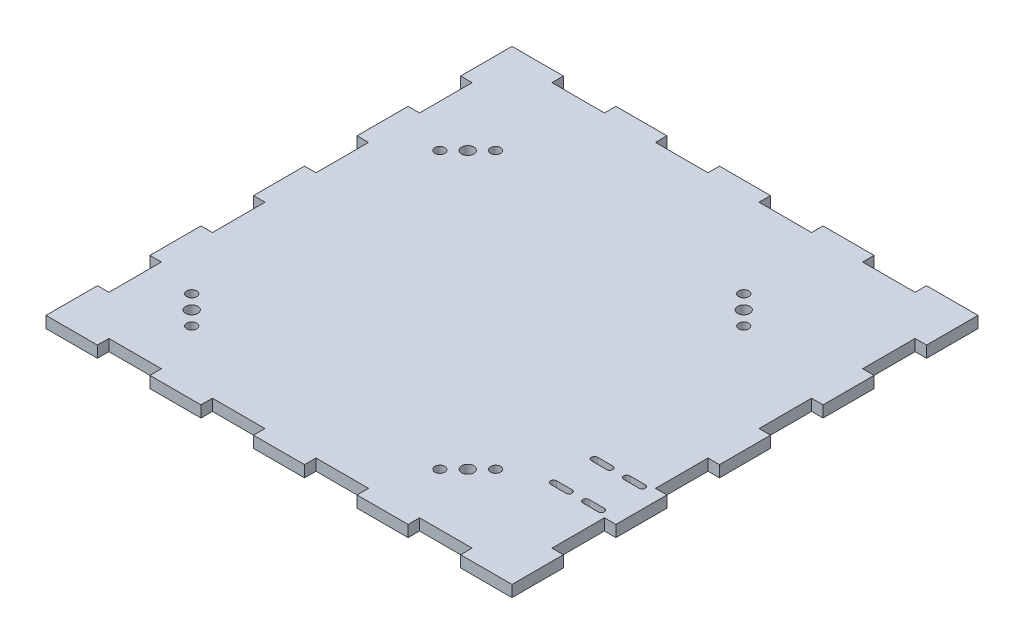
SolidWorks part; units mm, degrees
ref_plane "Front Plane" through (0, 0, 0) normal (0, 0, 1) x (1, 0, 0)
ref_plane "Top Plane" through (0, 0, 0) normal (0, 1, 0) x (1, 0, 0)
ref_plane "Right Plane" through (0, 0, 0) normal (1, 0, 0) x (0, 0, -1)
sketch "Board" plane through (0, 0, 0) normal (0, 1, 0) x (1, 0, 0)
  line L0 (45, -19.76) -> (50, -19.76)
  line L1 (-42.5, -42.5) -> (42.5, -42.5)
  line L2 (-42.5, -42.5) -> (-42.5, 42.5)
  line L3 (-42.5, 42.5) -> (42.5, 42.5)
  line L4 (42.5, -42.5) -> (42.5, 42.5)
  line L5 (-42.5, -42.5) -> (42.5, 42.5) construction
  line L6 (-42.5, 42.5) -> (42.5, -42.5) construction
  line L7 (-50.8, 48.85) -> (50.8, 48.85)
  line L8 (-50.8, 48.85) -> (-50.8, 42.5)
  line L9 (-50.8, 42.5) -> (50.8, 42.5)
  line L10 (50.8, 48.85) -> (50.8, 42.5)
  line L11 (45, -27.76) -> (50, -27.76)
  line L12 (47.5, -27.76) -> (47.5, -19.76) construction
  circle A0 centre (-38.5, 38.5) radius 1.6
  circle A1 centre (-38.5, -38.5) radius 1.6
  circle A2 centre (38.5, -38.5) radius 1.6
  circle A3 centre (38.5, 38.5) radius 1.6
  point P0 (0, 0)
  point P14 (0, 42.5)
  point P15 (0, 42.5)
  point P26 (47.5, -23.76)
  dimension "D4" = 3.2
  dimension "D1" = 85
  dimension "D2" = 85
  dimension "D3" = 4
  dimension "D5" = 6.35
  dimension "D6" = 101.6
  dimension "D7" = 18.74
  dimension "D8" = 8
  dimension "D9" = 5
  dimension "D10" = 5
sketch "Sketch2" plane through (0, 0, 0) normal (0, 1, 0) x (1, 0, 0)
  line L0 (-42.5, -42.5) -> (-42.5, 42.5) construction
  line L1 (-54.3, 66.65) -> (69.3, 66.65) construction
  line L2 (-54.3, 66.65) -> (-54.3, -56.95) construction
  line L3 (-54.3, -56.95) -> (69.3, -56.95) construction
  line L4 (69.3, 66.65) -> (69.3, -56.95) construction
  line L6 (42.5, -42.5) -> (42.5, 42.5) construction
  line L7 (-50.8, 48.85) -> (50.8, 48.85) construction
  line L8 (-57.5, 69.85) -> (-57.5, -60.15)
  line L9 (-57.5, -60.15) -> (72.5, -60.15)
  line L10 (72.5, 69.85) -> (72.5, -60.15)
  line L11 (-57.5, 69.85) -> (72.5, 69.85)
  circle A0 centre (-38.5, 38.5) radius 1.7
  circle A1 centre (-38.5, -38.5) radius 1.7
  circle A2 centre (38.5, -38.5) radius 1.7
  circle A3 centre (38.5, 38.5) radius 1.7
  point P16 (0, 0)
  dimension "D1" = 3.4
  dimension "D2" = 15
  dimension "D3" = 21
  dimension "D4" = 30
  dimension "D6" = 130
  dimension "D5" = 3.2
extrude "Boss-Extrude1" add sketch "Sketch2" along normal blind 3.2
sketch "Sketch5" plane through (0, 3.2, 0) normal (0, 1, 0) x (1, 0, 0)
  line L0 (34.6109, 42.3891) -> (42.3891, 34.6109) construction
  line L1 (72.5, -60.15) -> (72.5, 69.85) construction
  circle A0 centre (42.3891, 34.6109) radius 1.4
  circle A1 centre (34.6109, 42.3891) radius 1.4
  circle A2 centre (34.6109, -42.3891) radius 1.4
  circle A3 centre (42.3891, -34.6109) radius 1.4
  circle A4 centre (-42.3891, -34.6109) radius 1.4
  circle A5 centre (-34.6109, -42.3891) radius 1.4
  circle A6 centre (-34.6109, 42.3891) radius 1.4
  circle A7 centre (-42.3891, 34.6109) radius 1.4
  point P4 (38.5, 38.5)
  point P7 (-39.8129, -47.5911)
  point P8 (0, 0)
  point P23 (0, 0)
  dimension "D3" = 2.8
  dimension "D1" = 45
  dimension "D2" = 11
extrude "Cut-Extrude2" cut sketch "Sketch5" against normal up to next
sketch "Sketch4" plane through (0, 3.2, 0) normal (0, 1, 0) x (1, 0, 0)
  line L0 (72.5, 55.4056) -> (72.5, 40.9611)
  line L1 (72.5, -60.15) -> (72.5, 69.85) construction
  line L2 (72.5, 12.0722) -> (69.3, 12.0722)
  line L3 (69.3, 12.0722) -> (69.3, 26.5167)
  line L4 (69.3, 26.5167) -> (72.5, 26.5167)
  line L5 (72.5, 26.5167) -> (72.5, 12.0722)
  line L6 (72.5, -16.8167) -> (69.3, -16.8167)
  line L7 (69.3, -16.8167) -> (69.3, -2.3722)
  line L8 (69.3, -2.3722) -> (72.5, -2.3722)
  line L9 (72.5, -2.3722) -> (72.5, -16.8167)
  line L10 (72.5, 40.9611) -> (69.3, 40.9611)
  line L11 (69.3, 40.9611) -> (69.3, 55.4056)
  line L12 (69.3, 55.4056) -> (72.5, 55.4056)
  line L13 (72.5, -45.7056) -> (69.3, -45.7056)
  line L14 (69.3, -45.7056) -> (69.3, -31.2611)
  line L15 (69.3, -31.2611) -> (72.5, -31.2611)
  line L16 (72.5, -31.2611) -> (72.5, -45.7056)
  line L17 (72.5, 40.9611) -> (72.5, 12.0722) construction
  line L18 (69.3, -45.7056) -> (69.3, -60.15) construction
  line L19 (-57.5, -60.15) -> (72.5, -60.15) construction
  line L20 (69.3, -31.2611) -> (69.3, -16.8167) construction
  line L21 (72.5, 69.85) -> (-57.5, 69.85) construction
  line L42 (-57.5, 69.85) -> (72.5, -60.15) construction
  line L66 (-43.0556, -60.15) -> (-43.0556, -56.95)
  line L67 (-43.0556, -56.95) -> (-28.6111, -56.95)
  line L68 (-28.6111, -56.95) -> (-28.6111, -60.15)
  line L91 (69.3, -2.3722) -> (69.3, 12.0722) construction
  line L92 (69.3, 26.5167) -> (69.3, 40.9611) construction
  line L93 (69.3, 55.4056) -> (69.3, 69.85) construction
  line L94 (-28.6111, -60.15) -> (-43.0556, -60.15)
  line L95 (-14.1667, -60.15) -> (-14.1667, -56.95)
  line L96 (-14.1667, -56.95) -> (0.2778, -56.95)
  line L97 (0.2778, -56.95) -> (0.2778, -60.15)
  line L103 (0.2778, -60.15) -> (-14.1667, -60.15)
  line L108 (14.7222, -60.15) -> (14.7222, -56.95)
  line L113 (14.7222, -56.95) -> (29.1667, -56.95)
  line L118 (29.1667, -56.95) -> (29.1667, -60.15)
  line L119 (29.1667, -60.15) -> (14.7222, -60.15)
  line L120 (58.0556, -60.15) -> (43.6111, -60.15)
  line L121 (43.6111, -60.15) -> (43.6111, -56.95)
  line L125 (43.6111, -56.95) -> (58.0556, -56.95)
  line L126 (58.0556, -56.95) -> (58.0556, -60.15)
  line L127 (-57.5, 55.4056) -> (-54.3, 55.4056)
  line L128 (-54.3, 55.4056) -> (-54.3, 40.9611)
  line L129 (-54.3, 40.9611) -> (-57.5, 40.9611)
  line L130 (-57.5, 40.9611) -> (-57.5, 55.4056)
  line L131 (-57.5, 26.5167) -> (-54.3, 26.5167)
  line L132 (-54.3, 26.5167) -> (-54.3, 12.0722)
  line L133 (-54.3, 12.0722) -> (-57.5, 12.0722)
  line L134 (-57.5, 12.0722) -> (-57.5, 26.5167)
  line L135 (-57.5, -2.3722) -> (-54.3, -2.3722)
  line L136 (-54.3, -2.3722) -> (-54.3, -16.8167)
  line L137 (-54.3, -16.8167) -> (-57.5, -16.8167)
  line L138 (-57.5, -16.8167) -> (-57.5, -2.3722)
  line L139 (-57.5, -45.7056) -> (-57.5, -31.2611)
  line L140 (-57.5, -31.2611) -> (-54.3, -31.2611)
  line L141 (-54.3, -31.2611) -> (-54.3, -45.7056)
  line L142 (-54.3, -45.7056) -> (-57.5, -45.7056)
  line L143 (58.0556, 69.85) -> (58.0556, 66.65)
  line L144 (58.0556, 66.65) -> (43.6111, 66.65)
  line L145 (43.6111, 66.65) -> (43.6111, 69.85)
  line L146 (43.6111, 69.85) -> (58.0556, 69.85)
  line L147 (29.1667, 69.85) -> (29.1667, 66.65)
  line L148 (29.1667, 66.65) -> (14.7222, 66.65)
  line L149 (14.7222, 66.65) -> (14.7222, 69.85)
  line L150 (14.7222, 69.85) -> (29.1667, 69.85)
  line L151 (0.2778, 69.85) -> (0.2778, 66.65)
  line L152 (0.2778, 66.65) -> (-14.1667, 66.65)
  line L153 (-14.1667, 66.65) -> (-14.1667, 69.85)
  line L154 (-14.1667, 69.85) -> (0.2778, 69.85)
  line L155 (-43.0556, 69.85) -> (-28.6111, 69.85)
  line L156 (-28.6111, 69.85) -> (-28.6111, 66.65)
  line L157 (-28.6111, 66.65) -> (-43.0556, 66.65)
  line L158 (-43.0556, 66.65) -> (-43.0556, 69.85)
  point P27 (7.5, 4.85)
  point P81 (7.5, 4.85)
  dimension "D4" = 3.2
  dimension "D1" = 4
  dimension "D2" = 4
extrude "Cut-Extrude1" cut sketch "Sketch4" against normal through all
sketch "Sketch6" plane through (0, 3.2, 0) normal (0, 1, 0) x (1, 0, 0)
  line L0 (67, -29.7389) -> (62.7, -29.7389) construction
  line L1 (67, -30.5889) -> (62.7, -30.5889)
  line L2 (67, -28.8889) -> (62.7, -28.8889)
  line L3 (58, -29.7389) -> (53.7, -29.7389) construction
  line L4 (58, -30.5889) -> (53.7, -30.5889)
  line L5 (58, -28.8889) -> (53.7, -28.8889)
  line L6 (72.5, -24.0389) -> (-49927.5, -24.0389) construction
  line L7 (72.5, -31.2611) -> (72.5, -16.8167) construction
  line L8 (58, -18.3389) -> (53.7, -18.3389) construction
  line L9 (58, -17.4889) -> (53.7, -17.4889)
  line L10 (58, -19.1889) -> (53.7, -19.1889)
  line L11 (67, -18.3389) -> (62.7, -18.3389) construction
  line L12 (67, -17.4889) -> (62.7, -17.4889)
  line L13 (67, -19.1889) -> (62.7, -19.1889)
  arc A0 (67, -30.5889) -> (67, -28.8889) centre (67, -29.7389) ccw
  arc A1 (62.7, -28.8889) -> (62.7, -30.5889) centre (62.7, -29.7389) ccw
  arc A2 (58, -30.5889) -> (58, -28.8889) centre (58, -29.7389) ccw
  arc A3 (53.7, -28.8889) -> (53.7, -30.5889) centre (53.7, -29.7389) ccw
  arc A4 (58, -17.4889) -> (58, -19.1889) centre (58, -18.3389) cw
  arc A5 (53.7, -19.1889) -> (53.7, -17.4889) centre (53.7, -18.3389) cw
  arc A6 (67, -17.4889) -> (67, -19.1889) centre (67, -18.3389) cw
  arc A7 (62.7, -19.1889) -> (62.7, -17.4889) centre (62.7, -18.3389) cw
  point P2 (64.85, -29.7389)
  point P7 (55.85, -29.7389)
  point P18 (72.5, -24.0389)
  point P21 (55.85, -18.3389)
  point P28 (64.85, -18.3389)
  point P33 (57.7048, -30.8784)
  point P34 (66.542, -30.6806)
  dimension "D3" = 3
  dimension "D1" = 4.3
  dimension "D2" = 1.7
  dimension "D4" = 4.85
  dimension "D5" = 5.5
extrude "Cut-Extrude3" cut sketch "Sketch6" against normal up to next
other "Tolerance" face at (43.6111, 1.6, -68.25) face at (14.7222, 1.6, -68.25) face at (-14.1667, 1.6, -68.25) face at (-43.0556, 1.6, -68.25) face at (29.1667, 1.6, -68.25) face at (58.0556, 1.6, -68.25) face at (0.2778, 1.6, -68.25) face at (-28.6111, 1.6, -68.25) face at (-55.9, 1.6, -40.9611) face at (-55.9, 1.6, -55.4056) face at (-55.9, 1.6, -12.0722) face at (-55.9, 1.6, -26.5167) face at (-55.9, 1.6, 2.3722) face at (-55.9, 1.6, 16.8167) face at (-55.9, 1.6, 45.7056) face at (-55.9, 1.6, 31.2611) face at (-28.6111, 1.6, 58.55) face at (-43.0556, 1.6, 58.55) face at (-14.1667, 1.6, 58.55) face at (0.2778, 1.6, 58.55) face at (14.7222, 1.6, 58.55) face at (29.1667, 1.6, 58.55) face at (58.0556, 1.6, 58.55) face at (43.6111, 1.6, 58.55) face at (70.9, 1.6, 31.2611) face at (70.9, 1.6, 45.7056) face at (70.9, 1.6, 16.8167) face at (70.9, 1.6, 2.3722) face at (70.9, 1.6, -12.0722) face at (70.9, 1.6, -26.5167) face at (70.9, 1.6, -55.4056) face at (70.9, 1.6, -40.9611) parameters "D1"=0.1
equation "\"D5@Board\"=(1/4)*1in"
equation "\"D6@Board\"=4in"
equation "\"slot_depth\"= 3.2mm"
equation "\"slot_width_tolerance\"= 0.1mm"
equation "\"D4@Sketch4\"=\"slot_depth\""
